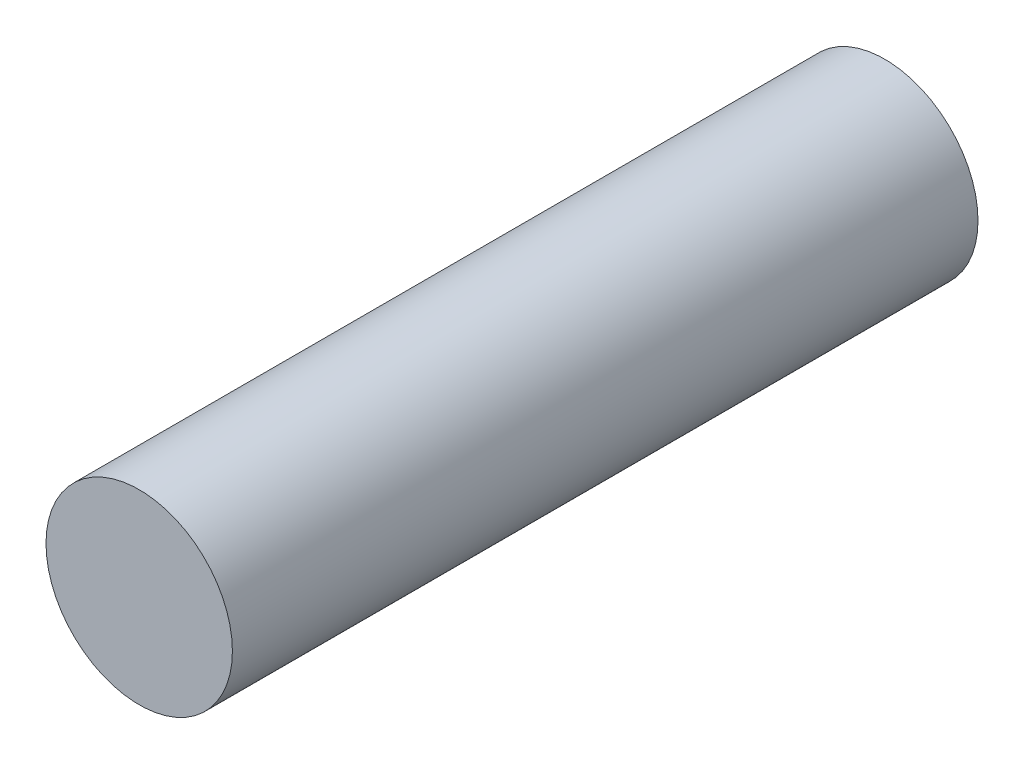
SolidWorks part; units mm, degrees
ref_plane "Front Plane" through (0, 0, 0) normal (0, 0, 1) x (1, 0, 0)
ref_plane "Top Plane" through (0, 0, 0) normal (0, 1, 0) x (1, 0, 0)
ref_plane "Right Plane" through (0, 0, 0) normal (1, 0, 0) x (0, 0, -1)
sketch "Sketch1" plane through (0, 0, 0) normal (0, 0, 1) x (1, 0, 0)
  circle A0 centre (0, 0) radius 17.5
  dimension "D1" = 35
extrude "Boss-Extrude1" add sketch "Sketch1" along normal mid plane 140
